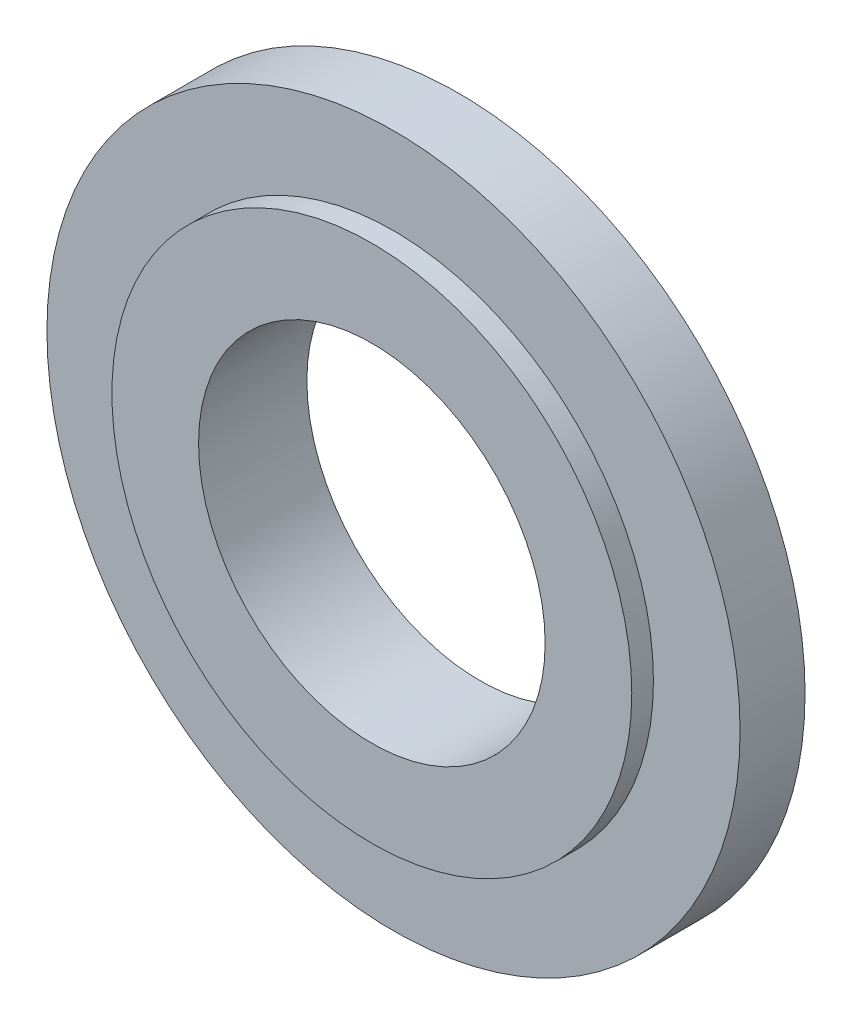
SolidWorks part; units mm, degrees
ref_plane "Спереди" through (0, 0, 0) normal (0, 0, 1) x (1, 0, 0)
ref_plane "Сверху" through (0, 0, 0) normal (0, 1, 0) x (1, 0, 0)
ref_plane "Справа" through (0, 0, 0) normal (1, 0, 0) x (0, 0, -1)
sketch "Эскиз1" plane through (0, 0, 0) normal (0, 0, 1) x (1, 0, 0)
  circle A0 centre (0, 0) radius 8
  circle A1 centre (0, 0) radius 4
  dimension "D1" = 16
  dimension "D2" = 8
extrude "Бобышка-Вытянуть1" add sketch "Эскиз1" along normal blind 1.5
sketch "Эскиз2" plane through (0, 0, 1.5) normal (0, 0, 1) x (1, 0, 0)
  circle A0 centre (0, 0) radius 6
  circle A1 centre (0, 0) radius 4
  circle A2 centre (0, 0) radius 4 construction
  dimension "D1" = 12
extrude "Бобышка-Вытянуть2" add sketch "Эскиз2" along normal blind 0.5
sketch "Эскиз3" plane through (0, 0, 0) normal (0, 0, -1) x (-1, 0, 0)
  circle A0 centre (0, 0) radius 6
  circle A1 centre (0, 0) radius 4
  circle A2 centre (0, 0) radius 4 construction
  dimension "D1" = 12
extrude "Бобышка-Вытянуть3" add sketch "Эскиз3" along normal blind 0.5
